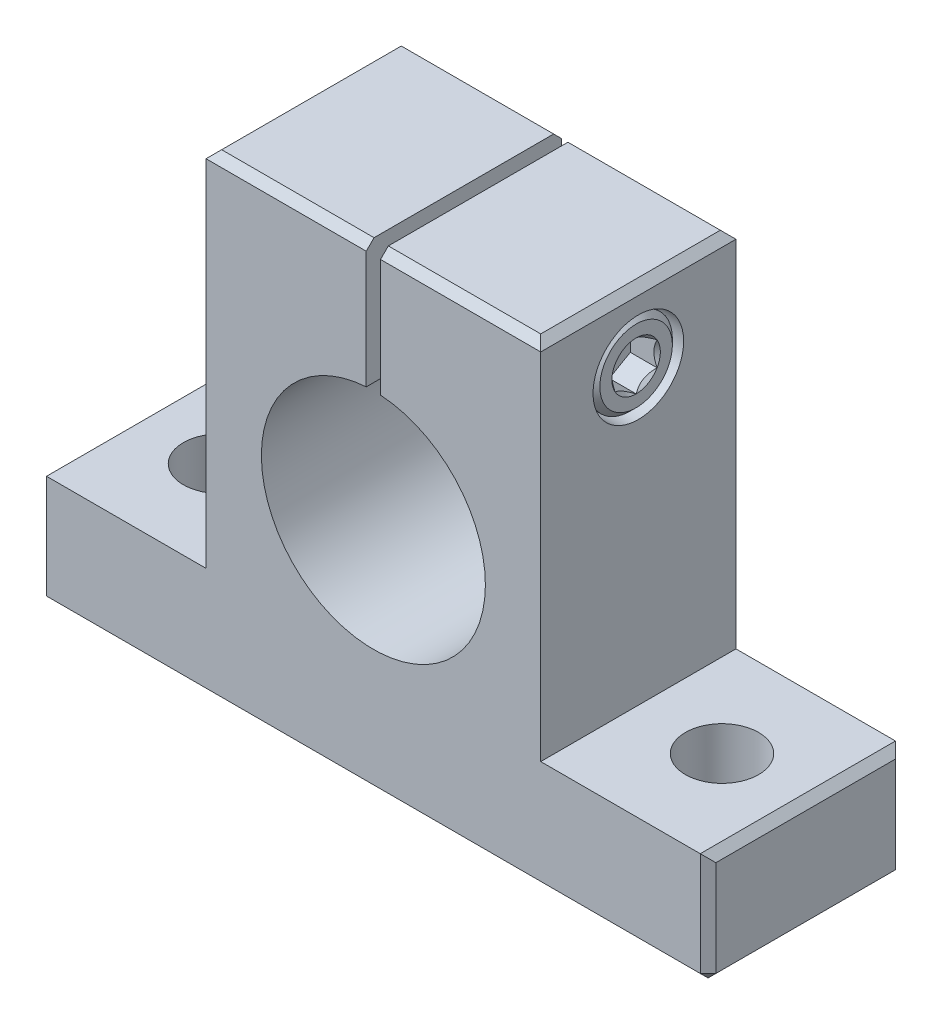
SolidWorks part; units mm, degrees
ref_plane "Front Plane" through (0, 0, 0) normal (0, 0, 1) x (1, 0, 0)
ref_plane "Top Plane" through (0, 0, 0) normal (0, 1, 0) x (1, 0, 0)
ref_plane "Right Plane" through (0, 0, 0) normal (1, 0, 0) x (0, 0, -1)
sketch "Sketch1" plane through (0, 0, 0) normal (0, 0, 1) x (1, 0, 0)
  line L0 (-38.1, 0) -> (38.1, 0)
  line L1 (-38.1, 0) -> (-38.1, 12.7)
  line L2 (-38.1, 12.7) -> (-19.05, 12.7)
  line L3 (-19.05, 12.7) -> (-19.05, 53.975)
  line L4 (-19.05, 53.975) -> (-0.8128, 53.975)
  line L5 (-0.8128, 53.975) -> (-0.8128, 39.7124)
  line L6 (0.8128, 39.7124) -> (0.8128, 53.975)
  line L7 (0.8128, 53.975) -> (19.05, 53.975)
  line L8 (19.05, 53.975) -> (19.05, 12.7)
  line L9 (19.05, 12.7) -> (38.1, 12.7)
  line L10 (38.1, 12.7) -> (38.1, 0)
  line L11 (0, 26.9875) -> (0, 0) construction
  arc A0 (-0.8128, 39.7124) -> (0.8128, 39.7124) centre (0, 26.9875) ccw
  circle A1 centre (0, 26.9875) radius 12.7508 construction
  dimension "D6" = 25.5016
  dimension "D1" = 76.2
  dimension "D2" = 12.7
  dimension "D3" = 53.975
  dimension "D4" = 38.1
  dimension "D5" = 26.9875
  dimension "D7" = 1.6256
extrude "Boss-Extrude1" add sketch "Sketch1" along normal mid plane 22.225
chamfer "Chamfer1" distance 0.889 angle 45 16 edges at (-38.1, 0, 0) (-38.1, 6.35, 11.1125) (0, 0, 11.1125) (-38.1, 6.35, -11.1125) (0, 0, -11.1125) (38.1, 6.35, -11.1125) (38.1, 0, 0) (38.1, 6.35, 11.1125) (-9.9314, 53.975, 11.1125) (-19.05, 53.975, 0) (-9.9314, 53.975, -11.1125) (9.9314, 53.975, -11.1125) (19.05, 53.975, 0) (9.9314, 53.975, 11.1125) (-38.1, 12.7, 0) (38.1, 12.7, 0)
sketch "Sketch2" plane through (0, 0, 0) normal (0, 1, 0) x (1, 0, 0)
  line L0 (-28.575, 0) -> (28.575, 0) construction
  circle A0 centre (-28.575, 0) radius 4.1656
  circle A1 centre (28.575, 0) radius 4.1656
  dimension "D2" = 8.3312
  dimension "D1" = 57.15
extrude "Cut-Extrude1" cut sketch "Sketch2" along normal through all
sketch "Sketch3" plane through (0, 0, 0) normal (0, 0, 1) x (1, 0, 0)
  line L0 (19.05, 46.0248) -> (-19.05, 46.0248) construction
  line L1 (-19.05, 46.0248) -> (-19.05, 49.1998)
  line L2 (-19.05, 49.1998) -> (-1.27, 49.1998)
  line L3 (-1.27, 49.1998) -> (-1.27, 49.2887)
  line L4 (-1.27, 49.2887) -> (12.446, 49.2887)
  line L5 (12.446, 49.2887) -> (12.446, 51.181)
  line L6 (12.446, 51.181) -> (19.05, 51.181)
  line L8 (19.05, 51.181) -> (19.05, 46.0248)
  line L9 (0.8128, 53.975) -> (19.05, 53.975) construction
  line L10 (-19.05, 12.7) -> (-19.05, 53.975) construction
  line L11 (19.05, 53.975) -> (19.05, 12.7) construction
  line L12 (19.05, 46.0248) -> (-19.05, 46.0248)
  dimension "D1" = 7.9502
  dimension "D2" = 6.35
  dimension "D3" = 6.5278
  dimension "D4" = 20.32
  dimension "D5" = 6.604
  dimension "D6" = 10.3124
revolve "Cut-Revolve1" cut sketch "Sketch3" angle 360 mid plane about L0
sketch "Sketch4" plane through (0, 0, 0) normal (0, 0, 1) x (1, 0, 0)
  line L0 (18.796, 46.0248) -> (-12.954, 46.0248) construction
  line L1 (-12.954, 46.0248) -> (-12.954, 49.1998)
  line L2 (-12.954, 49.1998) -> (12.446, 49.1998)
  line L3 (12.446, 49.1998) -> (12.446, 50.6603)
  line L4 (12.573, 50.7873) -> (18.161, 50.7873)
  line L5 (18.796, 50.1523) -> (18.796, 46.0248)
  line L6 (18.796, 46.0248) -> (-12.954, 46.0248)
  line L7 (12.446, 50.6603) -> (12.573, 50.7873)
  line L8 (18.161, 50.7873) -> (18.796, 50.1523)
  line L10 (18.161, 50.7873) -> (18.796, 50.7873) construction
  line L11 (18.796, 50.7873) -> (18.796, 50.1523) construction
  line L12 (12.446, 50.6603) -> (12.446, 50.7873) construction
  line L13 (12.446, 50.7873) -> (12.573, 50.7873) construction
  dimension "D1" = 6.35
  dimension "D2" = 25.4
  dimension "D3" = 6.35
  dimension "D4" = 9.525
  dimension "D5" = 0.635
  dimension "D6" = 0.127
revolve "Revolve1" add sketch "Sketch4" angle 360 mid plane about L0
sketch "Sketch5" plane through (18.796, 0, 0) normal (1, 0, 0) x (0, 0, -1)
  line L1 (0, 48.7818) -> (-2.3876, 47.4033)
  line L2 (-2.3876, 47.4033) -> (-2.3876, 44.6463)
  line L3 (-2.3876, 44.6463) -> (0, 43.2678)
  line L4 (0, 43.2678) -> (2.3876, 44.6463)
  line L5 (2.3876, 44.6463) -> (2.3876, 47.4033)
  line L6 (2.3876, 47.4033) -> (0, 48.7818)
  circle A0 centre (0, 46.0248) radius 2.3876 construction
  dimension "D1" = 4.7752
extrude "Cut-Extrude4" cut sketch "Sketch5" against normal blind 3.048
sketch "Sketch6" plane through (18.796, 0, 0) normal (1, 0, 0) x (0, 0, -1)
  circle A1 centre (0, 46.0248) radius 2.757
extrude "Cut-Extrude5" cut sketch "Sketch6" against normal through all draft 45
